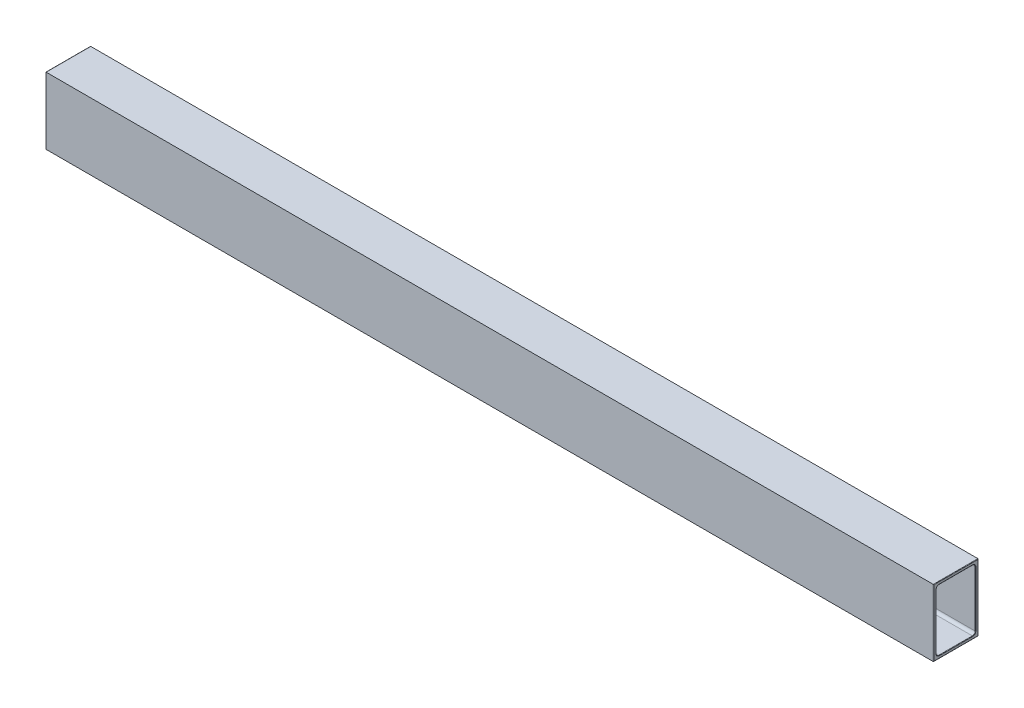
SolidWorks part; units mm, degrees
material "ASTM A500 Grade B Steel"
ref_plane "Front Plane" through (0, 0, 0) normal (0, 0, 1) x (1, 0, 0)
ref_plane "Top Plane" through (0, 0, 0) normal (0, 1, 0) x (1, 0, 0)
ref_plane "Right Plane" through (0, 0, 0) normal (1, 0, 0) x (0, 0, -1)
sketch "Sketch1" plane through (0, 0, 0) normal (1, 0, 0) x (0, 0, -1)
  line L0 (-95.25, 12.7) -> (-95.25, 139.7)
  line L1 (0, 0) -> (-101.6, 0)
  line L2 (0, 0) -> (0, 152.4)
  line L3 (0, 152.4) -> (-101.6, 152.4)
  line L4 (-101.6, 0) -> (-101.6, 152.4)
  line L5 (-12.7, 146.05) -> (-88.9, 146.05)
  line L6 (-6.35, 12.7) -> (-6.35, 139.7)
  line L7 (-12.7, 6.35) -> (-88.9, 6.35)
  line L8 (-95.25, 6.35) -> (-95.25, 146.05) construction
  line L9 (-6.35, 6.35) -> (-95.25, 6.35) construction
  line L10 (-6.35, 6.35) -> (-6.35, 146.05) construction
  line L11 (-6.35, 146.05) -> (-95.25, 146.05) construction
  arc A0 (-95.25, 12.7) -> (-88.9, 6.35) centre (-88.9, 12.7) ccw
  arc A1 (-6.35, 12.7) -> (-12.7, 6.35) centre (-12.7, 12.7) cw
  arc A2 (-12.7, 146.05) -> (-6.35, 139.7) centre (-12.7, 139.7) cw
  arc A3 (-95.25, 139.7) -> (-88.9, 146.05) centre (-88.9, 139.7) cw
  dimension "D4" = 6.35
  dimension "D1" = 152.4
  dimension "D2" = 101.6
  dimension "D3" = 6.35
extrude "Boss-Extrude1" add sketch "Sketch1" along normal blind 2022.605
fillet "Fillet1" radius 1 24 edges at (0, 152.4, 50.8) (2022.605, 8.2099, 8.2099) (2022.605, 76.2, 6.35) (2022.605, 144.1901, 8.2099) (2022.605, 146.05, 50.8) (2022.605, 144.1901, 93.3901) (2022.605, 76.2, 95.25) (2022.605, 8.2099, 93.3901) (2022.605, 6.35, 50.8) (2022.605, 0, 50.8) (2022.605, 76.2, 101.6) (2022.605, 152.4, 50.8) (2022.605, 76.2, 0) (0, 76.2, 95.25) (0, 144.1901, 93.3901) (0, 146.05, 50.8) (0, 144.1901, 8.2099) (0, 76.2, 6.35) (0, 8.2099, 8.2099) (0, 6.35, 50.8) (0, 8.2099, 93.3901) (0, 76.2, 101.6) (0, 0, 50.8) (0, 76.2, 0)
sketch "Sketch2" plane through (0, 0, 0) normal (0, -1, 0) x (1, 0, 0)
  line L0 (2021.605, 101.6) -> (1, 101.6) construction
  line L1 (858.9025, 101.6) -> (1163.7025, 101.6)
  line L2 (858.9025, 101.6) -> (858.9025, 0)
  line L3 (858.9025, 0) -> (1163.7025, 0)
  line L4 (1163.7025, 101.6) -> (1163.7025, 0)
  line L5 (2021.605, 0) -> (1, 0) construction
  point P8 (1011.3025, 101.6)
  point P9 (1011.3025, 101.6)
  dimension "D1" = 304.8
split line "Split Line1"
equation "\"D4@Sketch1\"=\"D3@Sketch1\""
